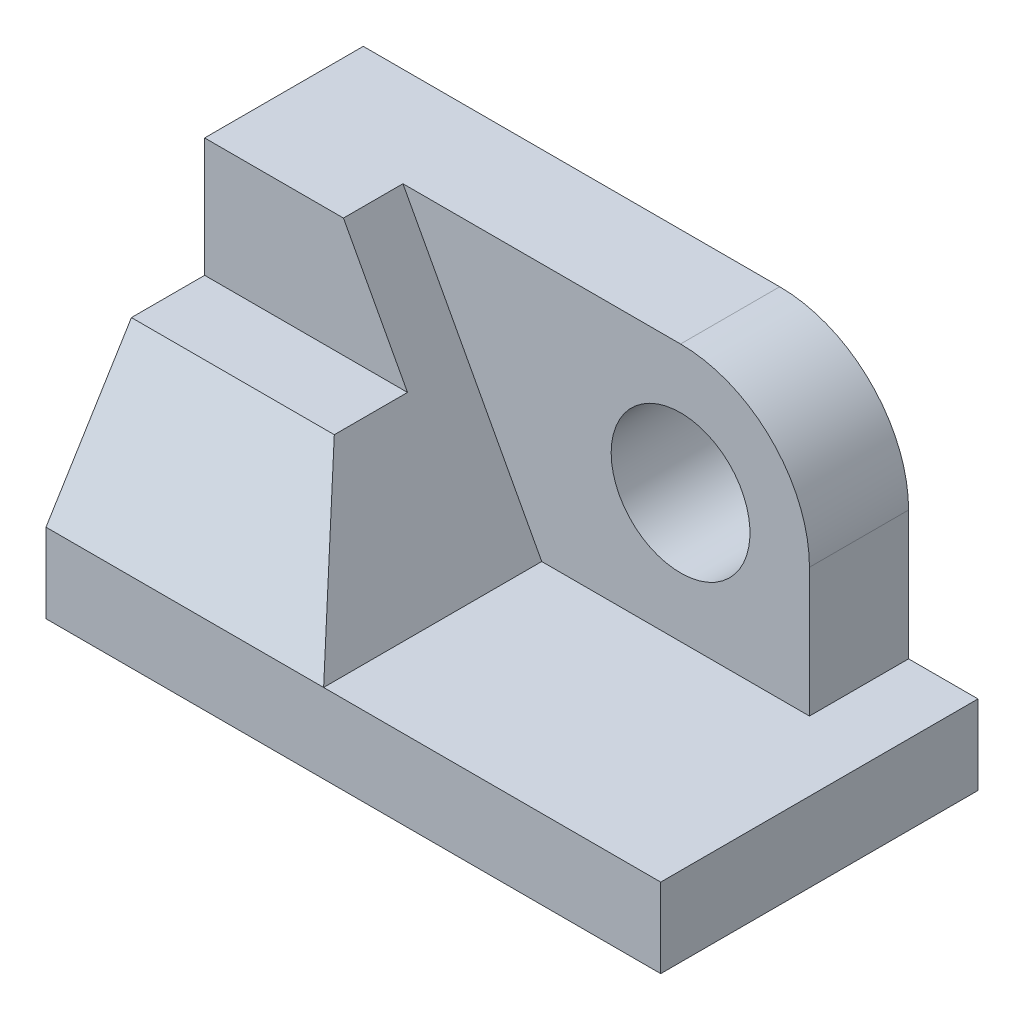
SolidWorks part; units mm, degrees
ref_plane "前视基准面" through (0, 0, 0) normal (0, 0, 1) x (1, 0, 0)
ref_plane "上视基准面" through (0, 0, 0) normal (0, 1, 0) x (1, 0, 0)
ref_plane "右视基准面" through (0, 0, 0) normal (1, 0, 0) x (0, 0, -1)
sketch "草图1" plane through (0, 0, 0) normal (0, 1, 0) x (1, 0, 0)
  line L1 (-31, 16) -> (31, 16)
  line L2 (-31, 16) -> (-31, -16)
  line L3 (-31, -16) -> (31, -16)
  line L4 (31, 16) -> (31, -16)
  line L5 (-31, 16) -> (31, -16) construction
  line L6 (-31, -16) -> (31, 16) construction
  point P0 (0, 0)
  dimension "D1" = 32
  dimension "D2" = 62
extrude "凸台-拉伸1" add sketch "草图1" along normal blind 8
sketch "草图2" plane through (0, 0, -16) normal (0, 0, -1) x (-1, 0, 0)
  line L0 (-24, 8) -> (-24, 21)
  line L1 (-31, 8) -> (31, 8) construction
  line L2 (-11, 34) -> (31, 34)
  line L3 (31, 34) -> (31, 8)
  line L4 (-31, 8) -> (-31, 0) construction
  line L5 (-31, 0) -> (31, 0) construction
  arc A0 (-11, 34) -> (-24, 21) centre (-11, 21) ccw
  circle A1 centre (-11, 21) radius 7
  line M4 (31, 8) -> (-31, 8)
  dimension "D1" = 13
  dimension "D2" = 13
  dimension "D3" = 20
  dimension "D4" = 34
extrude "凸台-拉伸2" add sketch "草图2" against normal blind 10 contours L2 A0 L0 L3 A1 M4
sketch "草图4" plane through (0, 34, 0) normal (0, 1, 0) x (1, 0, 0)
  line L0 (-31, 6) -> (-31, 0)
  line L1 (-31, 6) -> (-31, -16) construction
  line L2 (-31, 0) -> (-17, 0)
  line L3 (-17, 0) -> (-17, 6)
  line L4 (11, 6) -> (-31, 6) construction
  line L5 (-17, 6) -> (-31, 6)
  dimension "D1" = 6
  dimension "D2" = 14
sketch "草图5" plane through (0, 8, 0) normal (0, 1, 0) x (1, 0, 0)
  line L0 (-3, -16) -> (-3, 6)
  line L1 (-31, -16) -> (31, -16) construction
  line L2 (-31, 6) -> (24, 6) construction
  line L3 (-31, 6) -> (-31, -16) construction
  line L4 (-3, 6) -> (-31, 6)
  line L5 (-31, 6) -> (-31, -16)
  line L6 (-31, -16) -> (-3, -16)
  dimension "D1" = 28
loft "放样1" add profiles "草图5", "草图4"
ref_plane "基准面2" through (0, 22, 0) normal (0, 1, 0) x (1, 0, 0)
sketch "草图6" plane through (0, 22, 0) normal (0, 1, 0) x (1, 0, 0)
  line L0 (-31, 6) -> (-31, 0) construction
  line L1 (-9.6112, -8.4443) -> (-31, -8.4443)
  line L2 (-9.6112, -8.4443) -> (-9.6112, 0)
  line L3 (-9.6112, 0) -> (-31, 0)
  line L4 (-31, -8.4443) -> (-31, 0)
  line L5 (-9.6112, -8.4443) -> (-31, 0) construction
  line L6 (-9.6112, 0) -> (-31, -8.4443) construction
  line L7 (11, 16) -> (-31, 16) construction
  line L8 (-3, -16) -> (-17, 0) construction
  point P0 (-20.3056, -4.2222)
  point P9 (0, 0)
  dimension "D1" = 16
extrude "切除-拉伸1" cut sketch "草图6" along normal through all
